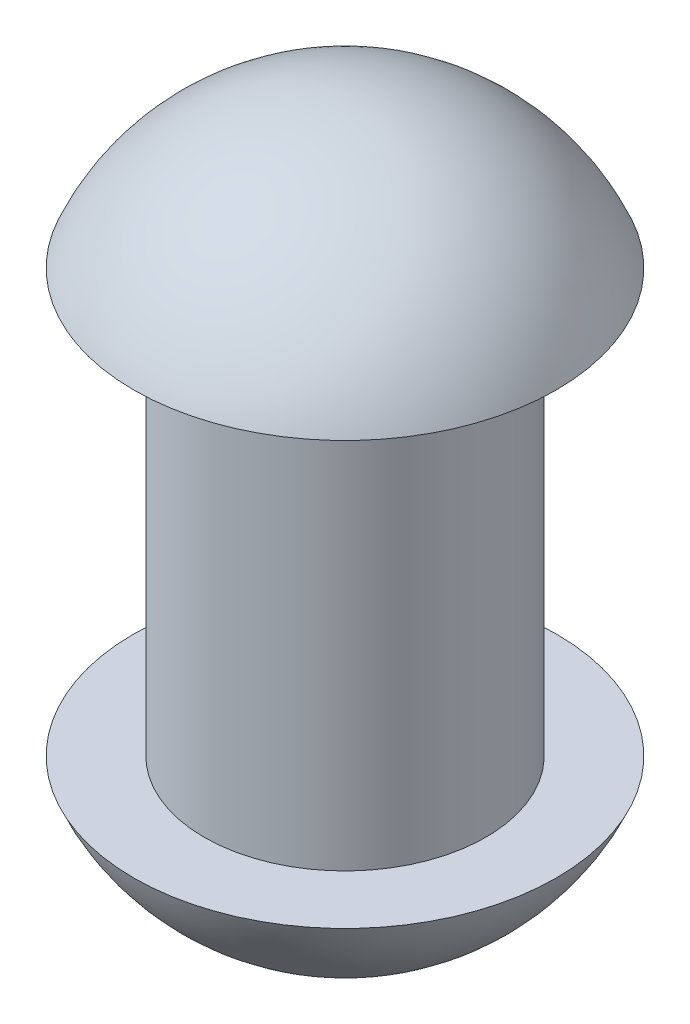
SolidWorks part; units mm, degrees
ref_plane "前视基准面" through (0, 0, 0) normal (0, 0, 1) x (1, 0, 0)
ref_plane "上视基准面" through (0, 0, 0) normal (0, 1, 0) x (1, 0, 0)
ref_plane "右视基准面" through (0, 0, 0) normal (1, 0, 0) x (0, 0, -1)
sketch "草图1" plane through (0, 0, 0) normal (0, 0, 1) x (1, 0, 0)
  line L0 (0, 0) -> (0, 5)
  line L1 (1.5, 4) -> (1, 4)
  line L2 (1, 4) -> (1, 1)
  line L3 (0, 2.5) -> (3.4155, 2.5) construction
  line L4 (1.5, 1) -> (1, 1)
  arc A0 (0, 5) -> (1.5, 4) centre (0, 3.375) cw
  arc A1 (0, 0) -> (1.5, 1) centre (0, 1.625) ccw
  point P12 (1, 2.5)
  dimension "D1" = 5
  dimension "D2" = 1.5
  dimension "D3" = 1
  dimension "D4" = 0.5
revolve "旋转1" add sketch "草图1" angle 360 about L0
